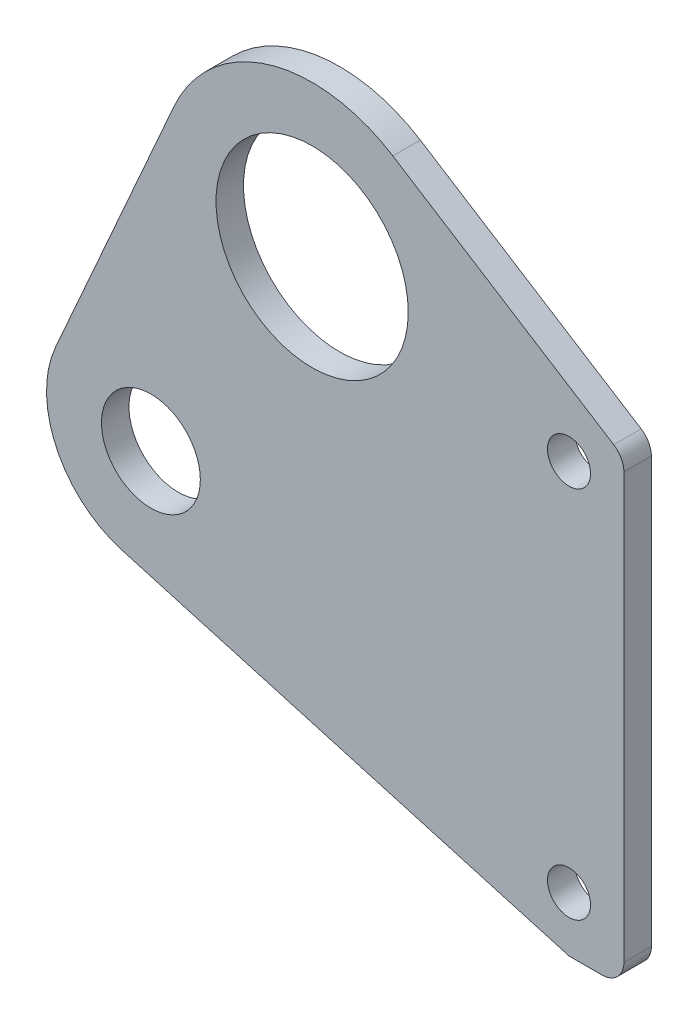
SolidWorks part; units mm, degrees
ref_plane "Front Plane" through (0, 0, 0) normal (1, 0, 0) x (0, 1, 0)
ref_plane "Top Plane" through (0, 0, 0) normal (0, 0, 1) x (0, 1, 0)
ref_plane "Right Plane" through (0, 0, 0) normal (0, 1, 0) x (-1, 0, 0)
sketch "Sketch1" plane through (0, 0, 0) normal (0, 0, 1) x (0, 1, 0)
  line L1 (-38.1, -38.1) -> (38.1, -38.1)
  line L2 (-38.1, -38.1) -> (-38.1, 38.1)
  line L3 (-38.1, 38.1) -> (38.1, 38.1)
  line L4 (38.1, -38.1) -> (38.1, 38.1)
  line L5 (-38.1, -38.1) -> (38.1, 38.1) construction
  line L6 (-38.1, 38.1) -> (38.1, -38.1) construction
  point P0 (0, 0)
  dimension "D1" = 76.2
  dimension "D2" = 76.2
extrude "Boss-Extrude1" add sketch "Sketch1" along normal blind 3.175
sketch "Sketch2" plane through (0, 0, 3.175) normal (0, 0, 1) x (1, 0, 0)
  line L0 (38.1, -38.1) -> (38.1, 38.1) construction
  line L1 (-38.1, -38.1) -> (38.1, -38.1) construction
  line L2 (11.3875, 31.8215) -> (38.1, 14.9274)
  line L3 (-13.9148, 24.1306) -> (-27.6201, -6.8345)
  line L4 (-19.9069, -23.317) -> (31.75, -38.1)
  line L8 (31.75, -38.1) -> (-38.1, -38.1)
  line L9 (-38.1, -38.1) -> (-38.1, 38.1)
  line L10 (-38.1, 38.1) -> (38.1, 38.1)
  line L11 (38.1, 38.1) -> (38.1, 14.9274)
  circle A0 centre (2.0535, 17.0629) radius 11.1125
  circle A1 centre (-16.5874, -11.7176) radius 5.715
  circle A2 centre (2.0535, 17.0629) radius 17.4625 construction
  circle A3 centre (-16.5874, -11.7176) radius 12.065 construction
  arc A4 (-13.9148, 24.1306) -> (11.3875, 31.8215) centre (2.0535, 17.0629) cw
  arc A5 (-27.6201, -6.8345) -> (-19.9069, -23.317) centre (-16.5874, -11.7176) ccw
  point P0 (2.0535, 17.0629)
  point P1 (31.75, 11.43)
  point P2 (31.75, -31.75)
  point P3 (-16.5874, -11.7176)
  dimension "D8" = 22.225
  dimension "D9" = 11.43
  dimension "D10" = 6.35
  dimension "D12" = 6.35
  dimension "D1" = 52.324
  dimension "D2" = 34.29
  dimension "D3" = 43.18
  dimension "D4" = 30.226
  dimension "D5" = 53.594
  dimension "D6" = 6.35
  dimension "D7" = 6.35
  dimension "D11" = 6.35
hole_wizard "#9 (0.196) Diameter Hole1" positions "Sketch2" profile "Sketch3" hole size "#9" standard "ANSI Inch"
sketch "Sketch3" plane through (31.75, -31.75, 3.175) normal (1, 0, 0) x (0, -1, 0)
  line L0 (0, 0) -> (0, 3.175)
  line L1 (0, 3.175) -> (2.4892, 3.175)
  line L2 (2.4892, 3.175) -> (2.4892, 0)
  line L5 (2.4892, 0) -> (0, 0)
  line L11 (0, -6.35) -> (0, 107.95) construction
  dimension "Thru Hole Dia." = 4.9784
  dimension "Thru Hole Depth" = 3.175
sketch "Sketch4" plane through (0, 0, 3.175) normal (0, 0, 1) x (1, 0, 0)
  circle A0 centre (-16.5874, -11.7176) radius 5.715 construction
  circle A1 centre (2.0535, 17.0629) radius 11.1125 construction
  circle A2 centre (-16.5874, -11.7176) radius 5.715
  circle A3 centre (2.0535, 17.0629) radius 11.1125
extrude "Cut-Extrude1" cut sketch "Sketch4" against normal blind 3.175
sketch "Sketch6" plane through (0, 0, 3.175) normal (0, 0, 1) x (1, 0, 0)
  line L0 (11.3875, 31.8215) -> (38.1, 14.9274) construction
  line L1 (-13.9148, 24.1306) -> (-27.6201, -6.8345) construction
  line L2 (-19.9069, -23.317) -> (31.75, -38.1) construction
  line L3 (31.75, -38.1) -> (-38.1, -38.1) construction
  line L4 (-38.1, -38.1) -> (-38.1, 38.1) construction
  line L5 (-38.1, 38.1) -> (38.1, 38.1) construction
  line L6 (38.1, 38.1) -> (38.1, 14.9274) construction
  line L7 (11.3875, 31.8215) -> (38.1, 14.9274)
  line L8 (-13.9148, 24.1306) -> (-27.6201, -6.8345)
  line L9 (-19.9069, -23.317) -> (31.75, -38.1)
  line L10 (31.75, -38.1) -> (-38.1, -38.1)
  line L11 (-38.1, -38.1) -> (-38.1, 38.1)
  line L12 (-38.1, 38.1) -> (38.1, 38.1)
  line L13 (38.1, 38.1) -> (38.1, 14.9274)
  arc A0 (11.3875, 31.8215) -> (-13.9148, 24.1306) centre (2.0535, 17.0629) ccw construction
  arc A1 (-27.6201, -6.8345) -> (-19.9069, -23.317) centre (-16.5874, -11.7176) ccw construction
  arc A2 (11.3875, 31.8215) -> (-13.9148, 24.1306) centre (2.0535, 17.0629) ccw
  arc A3 (-27.6201, -6.8345) -> (-19.9069, -23.317) centre (-16.5874, -11.7176) ccw
extrude "Cut-Extrude2" cut sketch "Sketch6" against normal blind 3.175
fillet "Fillet1" radius 2.54 2 edges at (38.1, -38.1, 1.5875) (38.1, 14.9274, 1.5875)
